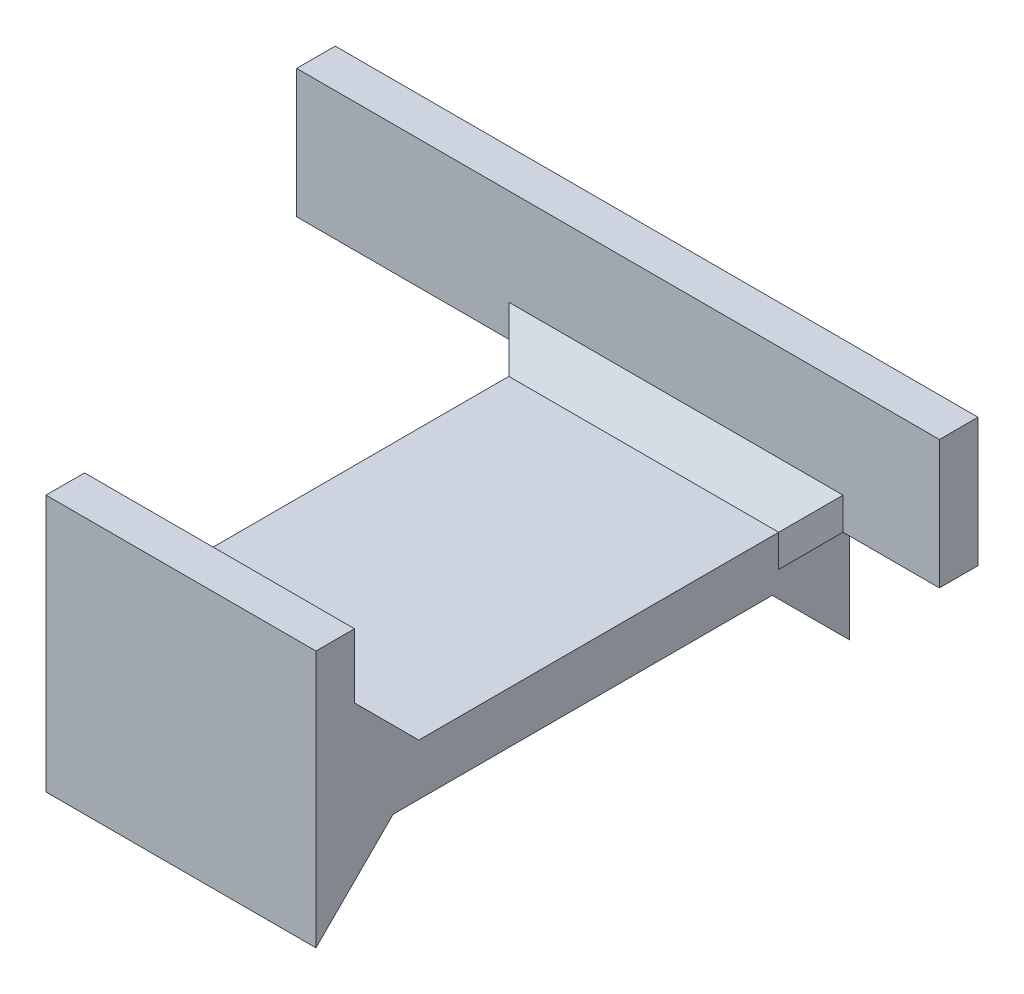
SolidWorks part; units mm, degrees
ref_plane "Front Plane" through (0, 0, 0) normal (0, 0, 1) x (1, 0, 0)
ref_plane "Top Plane" through (0, 0, 0) normal (0, 1, 0) x (1, 0, 0)
ref_plane "Right Plane" through (0, 0, 0) normal (1, 0, 0) x (0, 0, -1)
sketch "Sketch1" plane through (0, 0, 0) normal (0, 0, 1) x (1, 0, 0)
  line L1 (-10.5, -2) -> (10.5, -2)
  line L2 (-10.5, -2) -> (-10.5, 2)
  line L3 (-10.5, 2) -> (10.5, 2)
  line L4 (10.5, -2) -> (10.5, 2)
  line L5 (-10.5, -2) -> (10.5, 2) construction
  line L6 (-10.5, 2) -> (10.5, -2) construction
  point P0 (0, 0)
  dimension "D1" = 4
  dimension "D2" = 21
extrude "Boss-Extrude1" add sketch "Sketch1" along normal blind 41.5
sketch "Sketch2" plane through (0, 2, 0) normal (0, 1, 0) x (1, 0, 0)
  line L0 (-10.5, -41.5) -> (10.5, -41.5)
  line L1 (10.5, -41.5) -> (10.5, -38.5)
  line L2 (10.5, -41.5) -> (10.5, 0) construction
  line L3 (10.5, -38.5) -> (-10.5, -38.5)
  line L4 (-10.5, -41.5) -> (-10.5, 0) construction
  line L5 (-10.5, -38.5) -> (-10.5, -41.5)
  dimension "D1" = 3
extrude "Boss-Extrude2" add sketch "Sketch2" along normal blind 10
chamfer "Chamfer1" distance 5 angle 45 1 edges at (0, 2, 38.5)
ref_plane "Plane1" through (0, 0, 41.5) normal (0, 0, 1) x (1, 0, 0)
ref_plane "Plane2" through (10.5, 0, 0) normal (1, 0, 0) x (0, 0, -1)
sketch "Sketch4" plane through (10.5, 0, 0) normal (1, 0, 0) x (0, 0, -1)
  line L0 (-41.5, -2) -> (0, -2) construction
  line L1 (-35.5, -2) -> (-41.5, -8)
  line L2 (-41.5, 11.55) -> (-41.5, -11.55) construction
  line L3 (-41.5, -8) -> (-41.5, -2)
  line L4 (-41.5, -2) -> (-35.5, -2)
  line L5 (0, -2) -> (0, -8)
  line L6 (0, -8) -> (-6, -2)
  line L7 (-6, -2) -> (0, -2)
  dimension "D1" = 6
  dimension "D2" = 6
extrude "Boss-Extrude3" add sketch "Sketch4" against normal blind 21
sketch "Sketch6" plane through (0, 2, 0) normal (0, 1, 0) x (1, 0, 0)
  line L1 (-29.5, 0) -> (20.5, 0)
  line L2 (-29.5, 0) -> (-29.5, -3)
  line L3 (-29.5, -3) -> (20.5, -3)
  line L4 (20.5, 0) -> (20.5, -3)
  line L6 (10.5, 0) -> (-10.5, 0) construction
  line L7 (10.5, -16.9868) -> (10.5, 16.9868) construction
  line L8 (-10.5, -33.5) -> (-10.5, 0) construction
  dimension "D1" = 3
  dimension "D2" = 10
  dimension "D3" = 19
extrude "Boss-Extrude4" add sketch "Sketch6" along normal blind 10 contours L1 L4 L3 L2
chamfer "Chamfer3" distance 2.5 angle 45 1 edges at (0, 2, 3)
chamfer "Chamfer4" distance 2.5 angle 45 2 edges at (-10.5, 2, 1.5) (-10.5, 3.25, 3)
chamfer "Chamfer5" distance 2.5 angle 45 2 edges at (10.5, 2, 1.5) (10.5, 3.25, 3)
